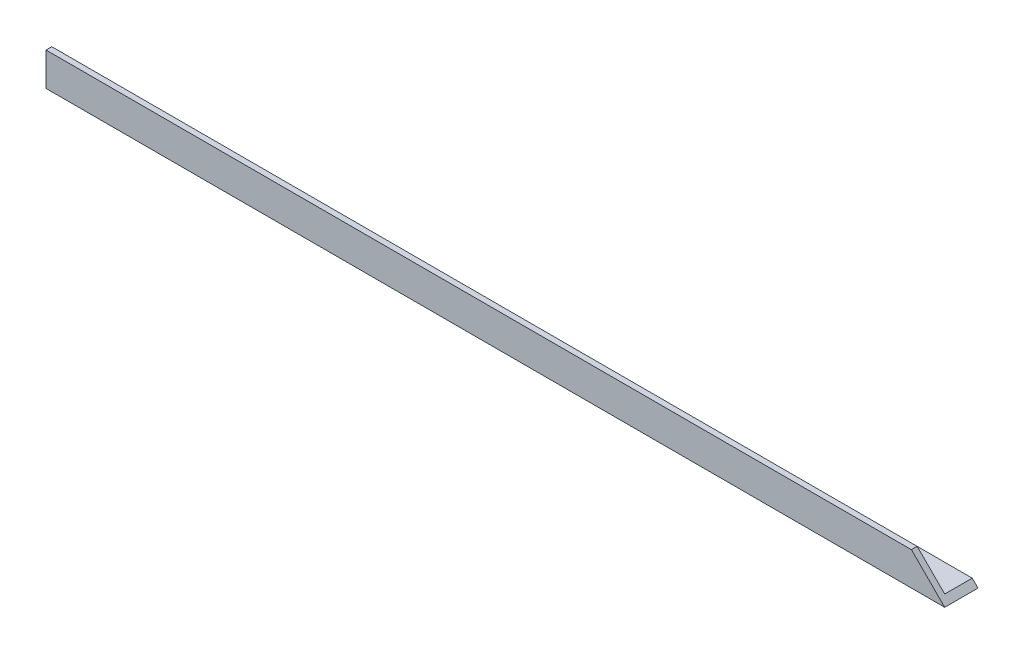
SolidWorks part; units mm, degrees
ref_plane "Front Plane" through (0, 0, 0) normal (0, 0, 1) x (1, 0, 0)
ref_plane "Top Plane" through (0, 0, 0) normal (0, 1, 0) x (1, 0, 0)
ref_plane "Right Plane" through (0, 0, 0) normal (1, 0, 0) x (0, 0, -1)
sketch "Sketch1" plane through (0, 0, 0) normal (1, 0, 0) x (0, 0, -1)
  line L0 (0, 0) -> (20, 0)
  line L1 (20, 0) -> (20, 3.4612)
  line L2 (20, 3.4612) -> (3.4612, 3.4612)
  line L3 (3.4612, 3.4612) -> (3.4612, 20)
  line L4 (3.4612, 20) -> (0, 20)
  line L5 (0, 20) -> (0, 0)
  dimension "D1" = 3.4612
  dimension "D2" = 20
extrude "Boss-Extrude1" add sketch "Sketch1" along normal blind 540
sketch "Sketch2" plane through (0, 0, 0) normal (0, 0, -1) x (1, 0, 0)
  line L4 (540, 0) -> (520, -20)
  line L5 (540, -20) -> (0, -20) construction
  line L6 (520, -20) -> (540, -20)
  line L7 (540, -20) -> (540, 0)
extrude "Cut-Extrude1" cut sketch "Sketch2" along normal through all
